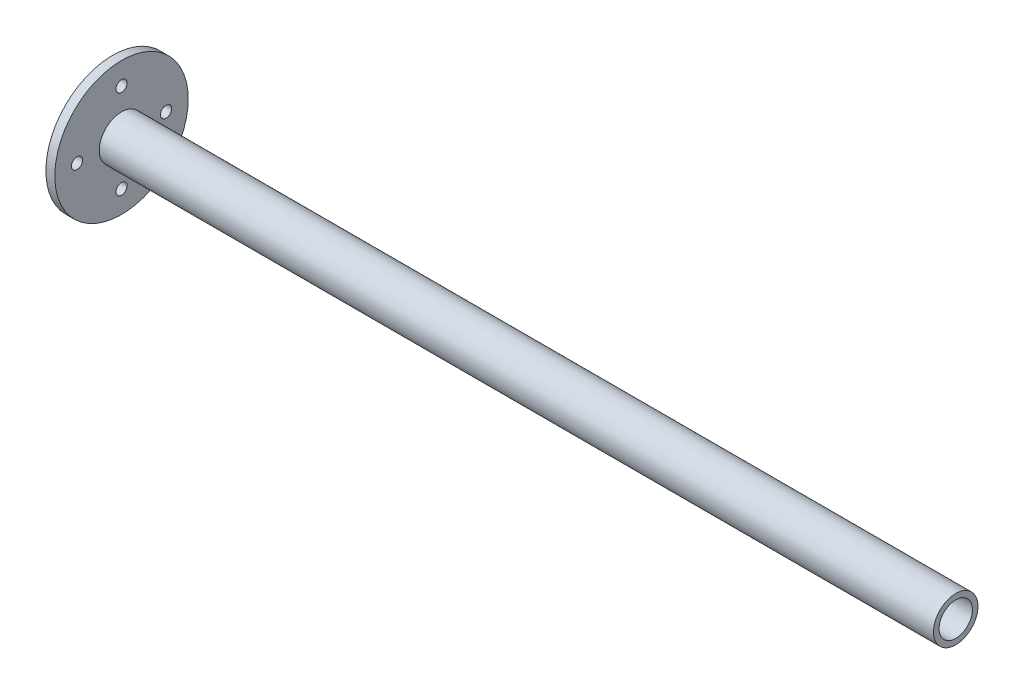
SolidWorks part; units mm, degrees
ref_plane "Front Plane" through (0, 0, 0) normal (0, 0, 1) x (1, 0, 0)
ref_plane "Top Plane" through (0, 0, 0) normal (0, 1, 0) x (1, 0, 0)
ref_plane "Right Plane" through (0, 0, 0) normal (1, 0, 0) x (0, 0, -1)
sketch "Sketch1" plane through (0, 0, 0) normal (1, 0, 0) x (0, 0, -1)
  circle A0 centre (0, 0) radius 12
  circle A1 centre (0, 0) radius 4
  circle A2 centre (0, 0) radius 3
  circle A3 centre (0, 8) radius 1
  circle A4 centre (8, 0) radius 1
  circle A5 centre (0, -8) radius 1
  circle A6 centre (-8, 0) radius 1
  point P16 (0, 0)
  dimension "D1" = 24
  dimension "D2" = 2
  dimension "D3" = 8
  dimension "D4" = 8
  dimension "D5" = 6
  dimension "D6" = 4
extrude "Boss-Extrude1" add sketch "Sketch1" along normal blind 1.6 contours A0 A6 A5 A4 A3 A1 | A1 A2 | A2
sketch "Sketch2" plane through (1.6, 0, 0) normal (1, 0, 0) x (0, 0, -1)
  circle A0 centre (0, 0) radius 3
  circle A1 centre (0, 0) radius 4
  dimension "D1" = 6
  dimension "D2" = 8
extrude "Boss-Extrude2" add sketch "Sketch2" along normal blind 150
sketch "Sketch3" plane through (0, 0, 0) normal (-1, 0, 0) x (0, 0, 1)
  circle A0 centre (0, 0) radius 3
  dimension "D1" = 6
extrude "Cut-Extrude1" cut sketch "Sketch3" against normal blind 150
